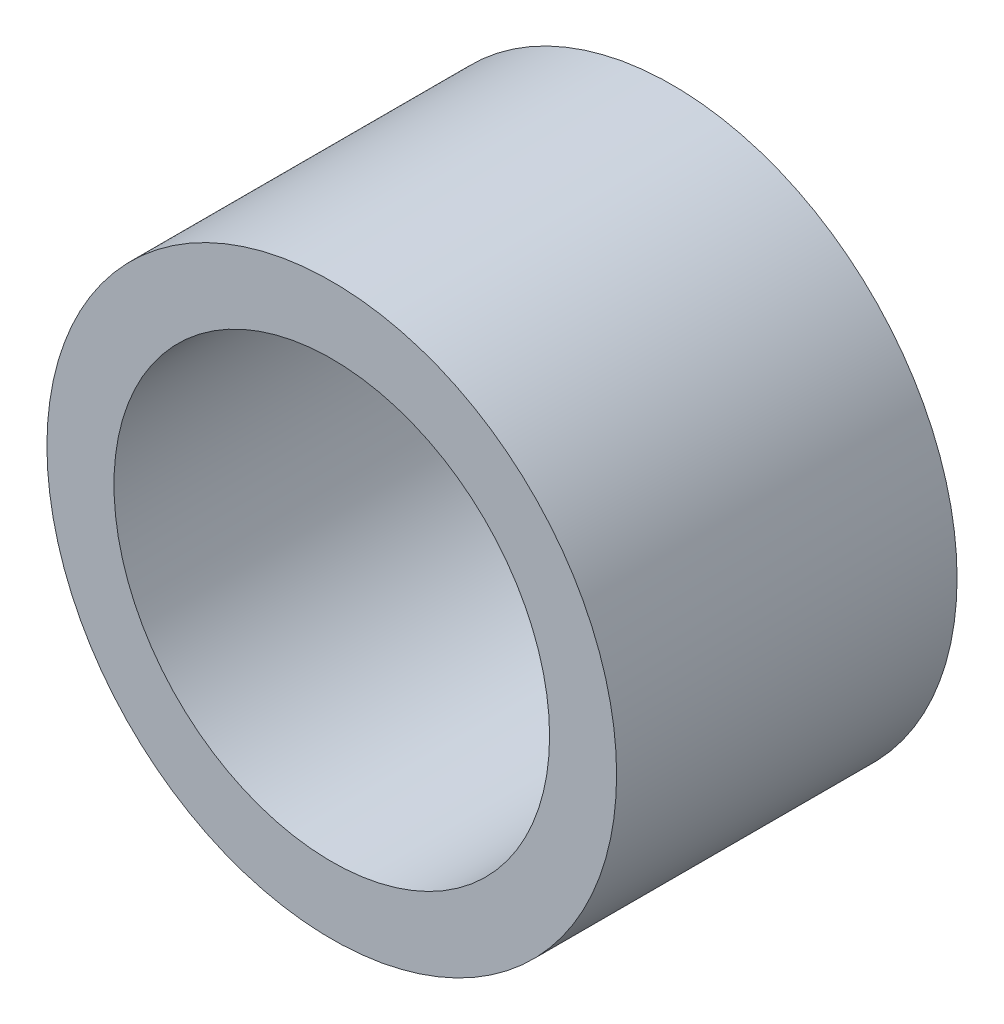
SolidWorks part; units mm, degrees
ref_plane "Front Plane" through (0, 0, 0) normal (0, 0, 1) x (1, 0, 0)
ref_plane "Top Plane" through (0, 0, 0) normal (0, 1, 0) x (1, 0, 0)
ref_plane "Right Plane" through (0, 0, 0) normal (1, 0, 0) x (0, 0, -1)
sketch "Sketch1" plane through (0, 0, 0) normal (0, 0, 1) x (1, 0, 0)
  circle A0 centre (0, 0) radius 3.25
  circle A1 centre (0, 0) radius 4.25
  dimension "D1" = 6.5
  dimension "D2" = 8.5
extrude "Boss-Extrude1" add sketch "Sketch1" along normal blind 5.08
